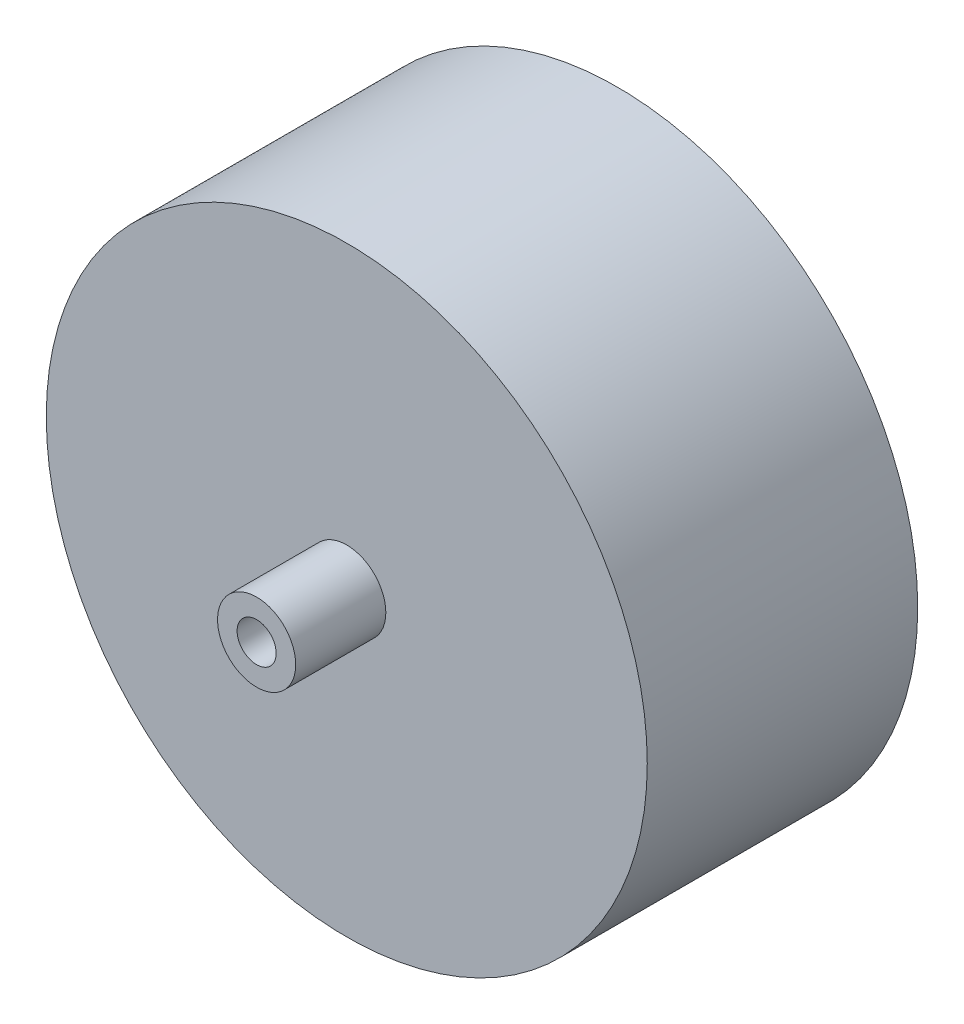
SolidWorks part; units mm, degrees
ref_plane "Front Plane" through (0, 0, 0) normal (0, 0, 1) x (1, 0, 0)
ref_plane "Top Plane" through (0, 0, 0) normal (0, 1, 0) x (1, 0, 0)
ref_plane "Right Plane" through (0, 0, 0) normal (1, 0, 0) x (0, 0, -1)
sketch "Sketch1" plane through (0, 0, 0) normal (0, 0, 1) x (1, 0, 0)
  circle A0 centre (0, 0) radius 50
  dimension "D1" = 100
extrude "Boss-Extrude1" add sketch "Sketch1" along normal blind 45
sketch "Sketch2" plane through (0, 0, 45) normal (0, 0, 1) x (1, 0, 0)
  circle A0 centre (0, 0) radius 6.5
  dimension "D1" = 13
extrude "Boss-Extrude2" add sketch "Sketch2" along normal blind 15
sketch "Sketch3" plane through (0, 0, 60) normal (0, 0, 1) x (1, 0, 0)
  circle A0 centre (0, 0) radius 3.25
  dimension "D1" = 6.5
extrude "Cut-Extrude1" cut sketch "Sketch3" against normal blind 13
